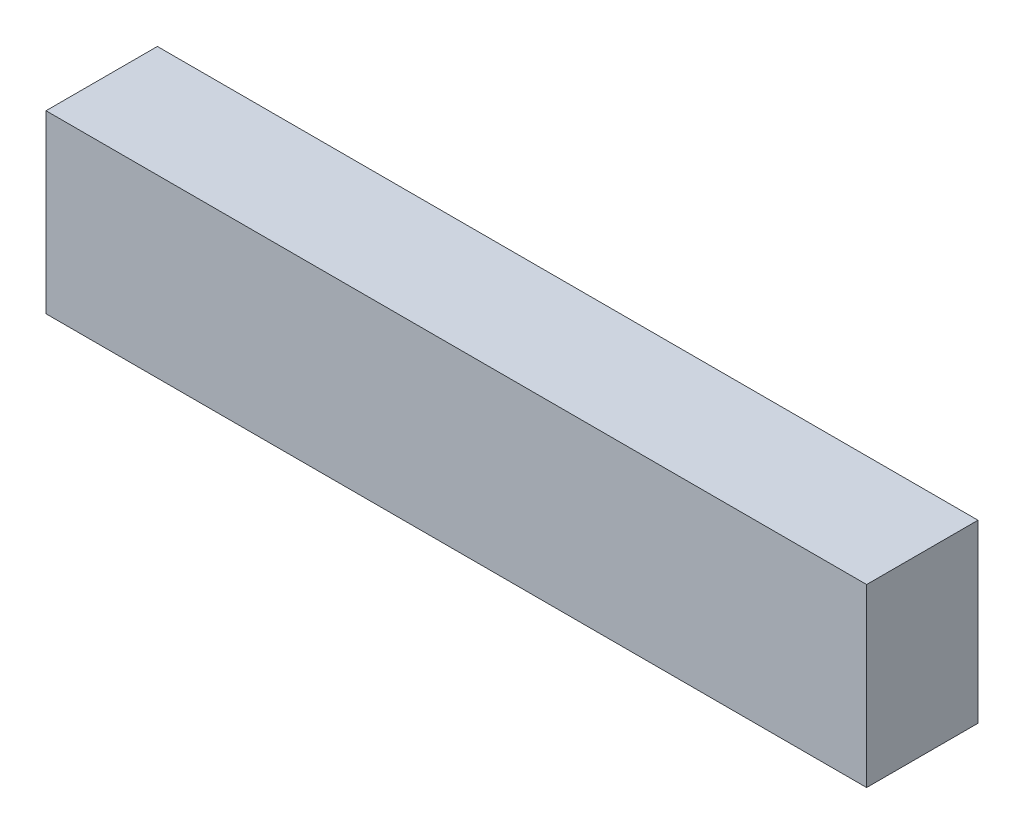
SolidWorks part; units mm, degrees
ref_plane "Front Plane" through (0, 0, 0) normal (1, 0, 0) x (0, 1, 0)
ref_plane "Top Plane" through (0, 0, 0) normal (0, 0, 1) x (0, 1, 0)
ref_plane "Right Plane" through (0, 0, 0) normal (0, 1, 0) x (-1, 0, 0)
sketch "Sketch2" plane through (0, 0, 0) normal (0, 0, 1) x (0, 1, 0)
  line L1 (-15, -70) -> (15, -70)
  line L2 (-15, -70) -> (-15, 70)
  line L3 (-15, 70) -> (15, 70)
  line L4 (15, -70) -> (15, 70)
  line L5 (-15, -70) -> (15, 70) construction
  line L6 (-15, 70) -> (15, -70) construction
  point P0 (0, 0)
  dimension "D1" = 30
  dimension "D2" = 140
extrude "Boss-Extrude1" add sketch "Sketch2" along normal blind 19
